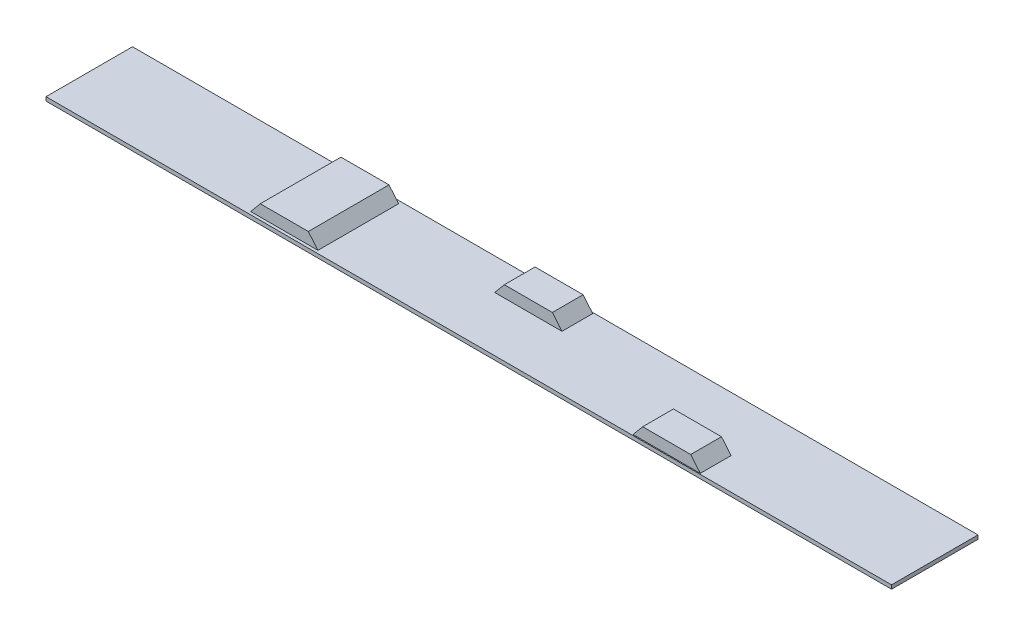
SolidWorks part; units mm, degrees
ref_plane "Front Plane" through (0, 0, 0) normal (0, 0, 1) x (1, 0, 0)
ref_plane "Top Plane" through (0, 0, 0) normal (0, 1, 0) x (1, 0, 0)
ref_plane "Right Plane" through (0, 0, 0) normal (1, 0, 0) x (0, 0, -1)
sketch "Sketch1" plane through (0, 0, 0) normal (0, 1, 0) x (1, 0, 0)
  line L1 (-1100, 112.5) -> (1100, 112.5)
  line L2 (-1100, 112.5) -> (-1100, -112.5)
  line L3 (-1100, -112.5) -> (1100, -112.5)
  line L4 (1100, 112.5) -> (1100, -112.5)
  line L5 (-1100, 112.5) -> (1100, -112.5) construction
  line L6 (-1100, -112.5) -> (1100, 112.5) construction
  point P0 (0, 0)
  dimension "D1" = 2200
  dimension "D2" = 225
extrude "Boss-Extrude1" add sketch "Sketch1" along normal blind 10
sketch "Sketch2" plane through (0, 0, 0) normal (0, 0, 1) x (1, 0, 0)
  line L0 (425, 10) -> (450, 40)
  line L1 (-1100, 10) -> (1100, 10) construction
  line L2 (450, 40) -> (575, 40)
  line L3 (575, 40) -> (600, 10)
  line L4 (425, 10) -> (600, 10)
  point P4 (512.5, 10)
  dimension "D1" = 175
  dimension "D2" = 125
  dimension "D3" = 30
  dimension "D4" = 512.5
extrude "Boss-Extrude2" add sketch "Sketch2" along normal blind 80 from offset 30
sketch "Sketch3" plane through (0, 0, 0) normal (0, 0, 1) x (1, 0, 0)
  line L0 (75, 40) -> (-50, 40)
  line L1 (-75, 10) -> (100, 10)
  line L2 (-50, 40) -> (-75, 10)
  line L3 (100, 10) -> (75, 40)
  line L4 (450, 40) -> (425, 10)
  line L5 (575, 40) -> (450, 40)
  line L6 (600, 10) -> (575, 40)
  line L7 (425, 10) -> (600, 10)
  line L8 (450, 40) -> (425, 10) construction
  line L9 (575, 40) -> (450, 40) construction
  line L10 (600, 10) -> (575, 40) construction
  line L11 (425, 10) -> (600, 10) construction
  dimension "D1" = 0
  dimension "D2" = 2
extrude "Boss-Extrude3" add sketch "Sketch3" against normal blind 80 from offset 30 offset against normal yes
sketch "Sketch4" plane through (0, 0, 0) normal (0, 0, 1) x (1, 0, 0)
  line L0 (-425, 40) -> (-550, 40)
  line L1 (-550, 40) -> (-575, 10)
  line L2 (-575, 10) -> (-400, 10)
  line L3 (-400, 10) -> (-425, 40)
  line L4 (75, 40) -> (-50, 40)
  line L5 (-50, 40) -> (-75, 10)
  line L6 (-75, 10) -> (100, 10)
  line L7 (100, 10) -> (75, 40)
  line L8 (75, 40) -> (-50, 40) construction
  line L9 (-50, 40) -> (-75, 10) construction
  line L10 (-75, 10) -> (100, 10) construction
  line L11 (100, 10) -> (75, 40) construction
  line L12 (75, 40) -> (-425, 40) construction
  dimension "D3" = 500
  dimension "D1" = 0
  dimension "D2" = 2
extrude "Boss-Extrude4" add sketch "Sketch4" along normal mid plane 210
